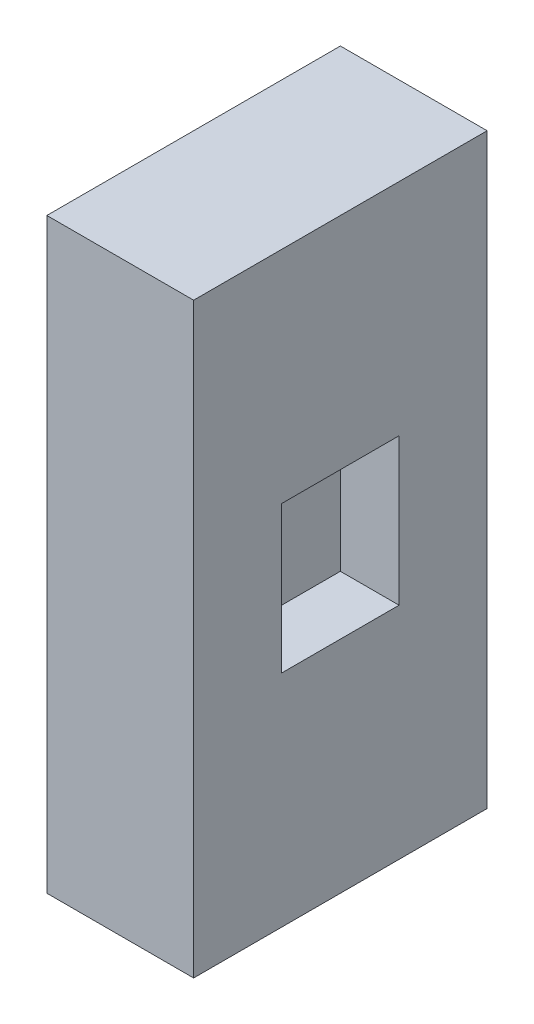
SolidWorks part; units mm, degrees
ref_plane "Front Plane" through (0, 0, 0) normal (0, 0, 1) x (1, 0, 0)
ref_plane "Top Plane" through (0, 0, 0) normal (0, 1, 0) x (1, 0, 0)
ref_plane "Right Plane" through (0, 0, 0) normal (1, 0, 0) x (0, 0, -1)
sketch "RectangleSketch" plane through (0, 0, 0) normal (1, 0, 0) x (0, 0, -1)
  line L1 (0, 0) -> (-20, 0)
  line L2 (0, 0) -> (0, 40)
  line L3 (0, 40) -> (-20, 40)
  line L4 (-20, 0) -> (-20, 40)
  dimension "width_mm" = 40
  dimension "height_mm" = 20
extrude "BlindBoss" add sketch "RectangleSketch" along normal blind 10 separate body
sketch "CutSketch" plane through (10, 0, 0) normal (1, 0, 0) x (0, 0, -1)
  line L1 (-6, 15) -> (-14, 15)
  line L2 (-6, 15) -> (-6, 25)
  line L3 (-6, 25) -> (-14, 25)
  line L4 (-14, 15) -> (-14, 25)
  dimension "cut_width_mm" = 10
  dimension "cut_height_mm" = 8
  dimension "cut_left_mm" = 15
  dimension "cut_bottom_mm" = 6
extrude "BlindCut" cut sketch "CutSketch" against normal blind 4
equation "\"cut_left_mm@CutSketch\" = (\"width_mm@RectangleSketch\" - \"cut_width_mm@CutSketch\") / 2"
equation "\"cut_bottom_mm@CutSketch\" = (\"height_mm@RectangleSketch\" - \"cut_height_mm@CutSketch\") / 2"
